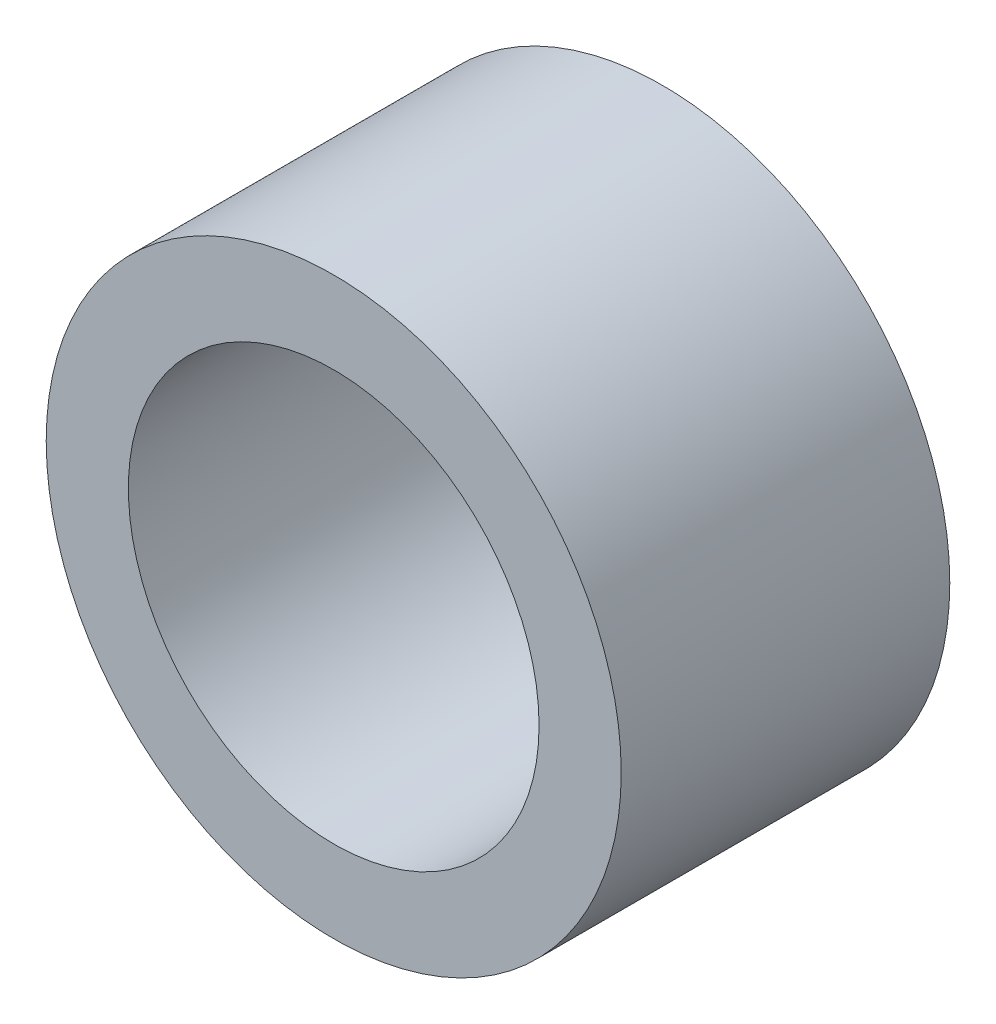
SolidWorks part; units mm, degrees
ref_plane "Alzado" through (0, 0, 0) normal (0, 0, 1) x (1, 0, 0)
ref_plane "Planta" through (0, 0, 0) normal (0, 1, 0) x (1, 0, 0)
ref_plane "Vista lateral" through (0, 0, 0) normal (1, 0, 0) x (0, 0, -1)
sketch "Croquis1" plane through (0, 0, 0) normal (0, 0, 1) x (1, 0, 0)
  circle A0 centre (0, 0) radius 3.5
  circle A1 centre (0, 0) radius 2.5
  dimension "D1" = 7
  dimension "D2" = 5
extrude "Saliente-Extruir1" add sketch "Croquis1" along normal blind 4
